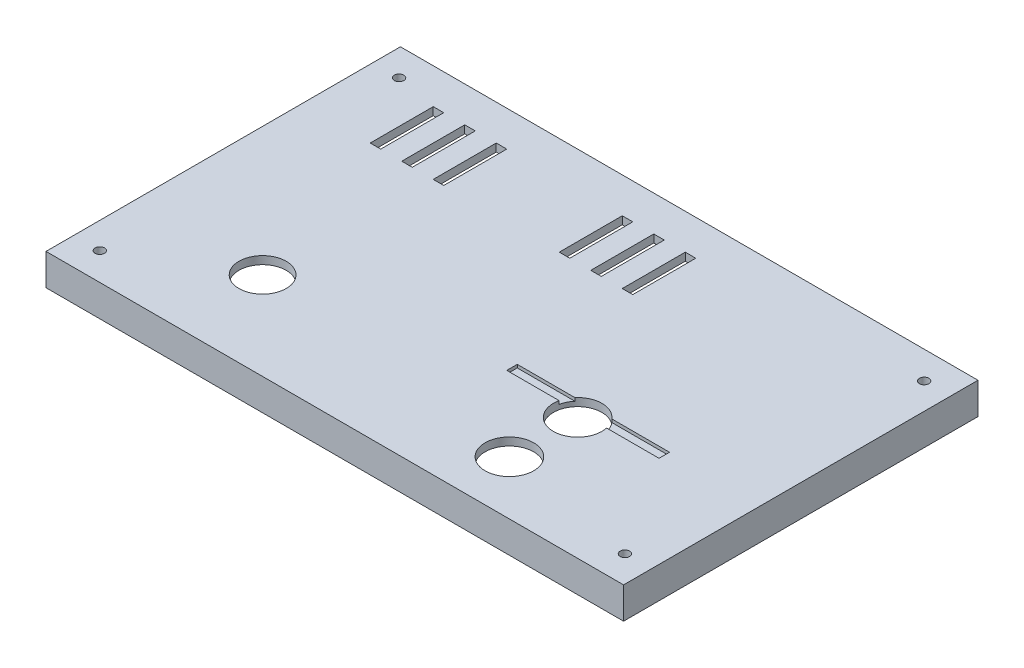
SolidWorks part; units mm, degrees
ref_plane "前视基准面" through (0, 0, 0) normal (0, 0, 1) x (1, 0, 0)
ref_plane "上视基准面" through (0, 0, 0) normal (0, 1, 0) x (1, 0, 0)
ref_plane "右视基准面" through (0, 0, 0) normal (1, 0, 0) x (0, 0, -1)
other "Configuration Table"
sketch "草图1" plane through (0, 0, 0) normal (0, 1, 0) x (1, 0, 0)
  line L1 (-110, -67.5) -> (110, -67.5)
  line L2 (-110, -67.5) -> (-110, 67.5)
  line L3 (-110, 67.5) -> (110, 67.5)
  line L4 (110, -67.5) -> (110, 67.5)
extrude "Lid_Top_3mm" add sketch "草图1" against normal blind 3
sketch "草图2" plane through (0, 0, 0) normal (0, 1, 0) x (1, 0, 0)
  line L0 (110, 67.5) -> (-110, 67.5) construction
  line L1 (-108, 65.5) -> (108, 65.5)
  line L2 (-108, 65.5) -> (-108, 67.5)
  line L3 (-108, 67.5) -> (108, 67.5)
  line L4 (108, 65.5) -> (108, 67.5)
extrude "Lid_Rim_Back" add sketch "草图2" against normal blind 12
sketch "草图3" plane through (0, 0, 0) normal (0, 1, 0) x (1, 0, 0)
  line L0 (-110, -67.5) -> (110, -67.5) construction
  line L1 (-108, -67.5) -> (108, -67.5)
  line L2 (-108, -67.5) -> (-108, -65.5)
  line L3 (-108, -65.5) -> (108, -65.5)
  line L4 (108, -67.5) -> (108, -65.5)
extrude "Lid_Rim_Front" add sketch "草图3" against normal blind 12
sketch "草图4" plane through (0, 0, 0) normal (0, 1, 0) x (1, 0, 0)
  line L1 (-110, -67.5) -> (-108, -67.5)
  line L2 (-110, -67.5) -> (-110, 67.5)
  line L3 (-110, 67.5) -> (-108, 67.5)
  line L4 (-108, -67.5) -> (-108, 67.5)
extrude "Lid_Rim_Left" add sketch "草图4" against normal blind 12
sketch "草图5" plane through (0, 0, 0) normal (0, 1, 0) x (1, 0, 0)
  line L0 (-110, -67.5) -> (110, -67.5) construction
  line L1 (108, -67.5) -> (110, -67.5)
  line L2 (108, -67.5) -> (108, 67.5)
  line L3 (108, 67.5) -> (110, 67.5)
  line L4 (110, -67.5) -> (110, 67.5)
extrude "Lid_Rim_Right" add sketch "草图5" against normal blind 12
sketch "草图6" plane through (0, 0, 0) normal (0, 1, 0) x (1, 0, 0)
  circle A0 centre (-100, -57) radius 1.8
extrude "Lid_Screw_Clearance_1" cut sketch "草图6" against normal blind 16
sketch "草图7" plane through (0, 0, 0) normal (0, 1, 0) x (1, 0, 0)
  circle A0 centre (100, -57) radius 1.8
extrude "Lid_Screw_Clearance_2" cut sketch "草图7" against normal blind 16
sketch "草图8" plane through (0, 0, 0) normal (0, 1, 0) x (1, 0, 0)
  circle A0 centre (-100, 57) radius 1.8
extrude "Lid_Screw_Clearance_3" cut sketch "草图8" against normal blind 16
sketch "草图9" plane through (0, 0, 0) normal (0, 1, 0) x (1, 0, 0)
  circle A0 centre (100, 57) radius 1.8
extrude "Lid_Screw_Clearance_4" cut sketch "草图9" against normal blind 16
sketch "草图10" plane through (0, 0, 0) normal (0, 1, 0) x (1, 0, 0)
  circle A0 centre (-61, -34) radius 9
extrude "OV5647_Lens_Opening_D18" cut sketch "草图10" against normal blind 4
sketch "草图11" plane through (0, 0, 0) normal (0, 1, 0) x (1, 0, 0)
  circle A0 centre (46, -47) radius 9.25
extrude "HC_SR04_Acoustic_Opening_1" cut sketch "草图11" against normal blind 4
sketch "草图12" plane through (0, 0, 0) normal (0, 1, 0) x (1, 0, 0)
  circle A0 centre (46, -21) radius 9.25
extrude "HC_SR04_Acoustic_Opening_2" cut sketch "草图12" against normal blind 4
sketch "草图13" plane through (0, 0, 0) normal (0, 1, 0) x (1, 0, 0)
  line L1 (17, -19) -> (75, -19)
  line L2 (17, -19) -> (17, -15)
  line L3 (17, -15) -> (75, -15)
  line L4 (75, -19) -> (75, -15)
extrude "HC_SR04_Alignment_Recess" cut sketch "草图13" against normal blind 1.2
sketch "草图14" plane through (0, 0, 0) normal (0, 1, 0) x (1, 0, 0)
  line L1 (-84, 30) -> (-80, 30)
  line L2 (-84, 30) -> (-84, 54)
  line L3 (-84, 54) -> (-80, 54)
  line L4 (-80, 30) -> (-80, 54)
extrude "Vent_Slot_1" cut sketch "草图14" against normal blind 4
sketch "草图15" plane through (0, 0, 0) normal (0, 1, 0) x (1, 0, 0)
  line L1 (-72, 30) -> (-68, 30)
  line L2 (-72, 30) -> (-72, 54)
  line L3 (-72, 54) -> (-68, 54)
  line L4 (-68, 30) -> (-68, 54)
extrude "Vent_Slot_2" cut sketch "草图15" against normal blind 4
sketch "草图16" plane through (0, 0, 0) normal (0, 1, 0) x (1, 0, 0)
  line L1 (-60, 30) -> (-56, 30)
  line L2 (-60, 30) -> (-60, 54)
  line L3 (-60, 54) -> (-56, 54)
  line L4 (-56, 30) -> (-56, 54)
extrude "Vent_Slot_3" cut sketch "草图16" against normal blind 4
sketch "草图17" plane through (0, 0, 0) normal (0, 1, 0) x (1, 0, 0)
  line L1 (-12, 30) -> (-8, 30)
  line L2 (-12, 30) -> (-12, 54)
  line L3 (-12, 54) -> (-8, 54)
  line L4 (-8, 30) -> (-8, 54)
extrude "Vent_Slot_4" cut sketch "草图17" against normal blind 4
sketch "草图18" plane through (0, 0, 0) normal (0, 1, 0) x (1, 0, 0)
  line L1 (0, 30) -> (4, 30)
  line L2 (0, 30) -> (0, 54)
  line L3 (0, 54) -> (4, 54)
  line L4 (4, 30) -> (4, 54)
extrude "Vent_Slot_5" cut sketch "草图18" against normal blind 4
sketch "草图19" plane through (0, 0, 0) normal (0, 1, 0) x (1, 0, 0)
  line L1 (12, 30) -> (16, 30)
  line L2 (12, 30) -> (12, 54)
  line L3 (12, 54) -> (16, 54)
  line L4 (16, 30) -> (16, 54)
extrude "Vent_Slot_6" cut sketch "草图19" against normal blind 4
